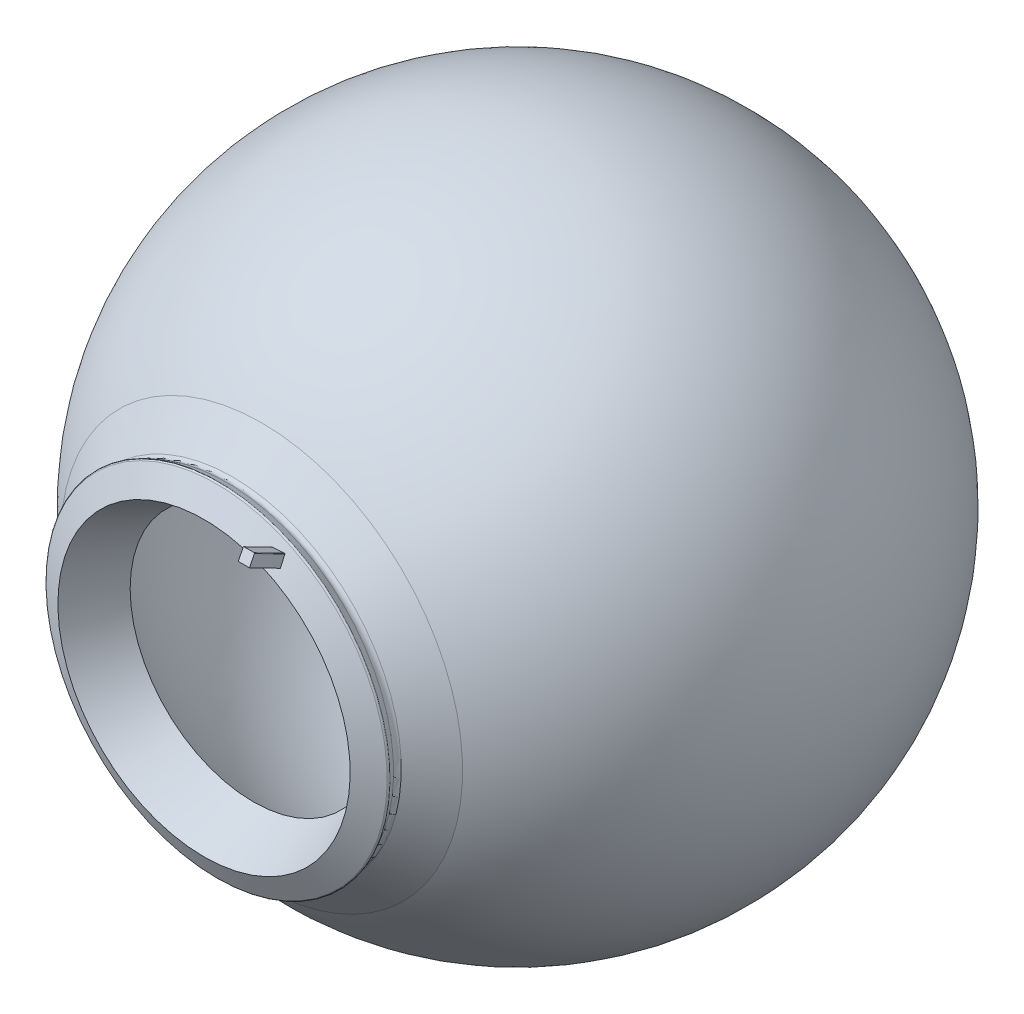
SolidWorks part; units mm, degrees
ref_plane "Front Plane" through (0, 0, 0) normal (0, 0, 1) x (1, 0, 0)
ref_plane "Top Plane" through (0, 0, 0) normal (0, 1, 0) x (1, 0, 0)
ref_plane "Right Plane" through (0, 0, 0) normal (1, 0, 0) x (0, 0, -1)
sketch "Sphere Sketch" plane through (0, 0, 0) normal (1, 0, 0) x (0, 0, -1)
  line L0 (-495, 0) -> (0, 0) construction
  line L1 (-495, 230.6517) -> (0, 0) construction
  line L2 (-495, 230.6517) -> (-495, 0) construction
  line L3 (-552.5581, 257.4717) -> (-495, 230.6517)
  line L5 (0, 0) -> (531.6016, 0) construction
  line L6 (-587.2743, 273.6481) -> (-552.5581, 257.4717)
  line L8 (-574.9857, 296.2531) -> (0, 0) construction
  line L9 (-856.9957, 1420.5972) -> (-601.6623, 1420.5972) construction
  line L11 (-563.7113, 319.3806) -> (-587.2743, 273.6481)
  line L12 (-479.5063, 376.4118) -> (-533.6922, 315.7211)
  line L13 (531.6016, 125) -> (531.6016, 0) construction
  line L14 (0, 0) -> (531.6016, 125) construction
  line L15 (-559.6704, 320.6734) -> (-545.714, 313.4825)
  line L17 (531.6016, 125) -> (593.4157, 139.5349)
  line L18 (593.4157, 139.5349) -> (618.1413, 145.3488)
  line L19 (618.1413, 145.3488) -> (568.3844, 220.3438)
  arc A2 (531.6016, 125) -> (-495, 230.6517) centre (0, 0) ccw
  arc A3 (-563.5933, 319.5888) -> (-587.2743, 273.6481) centre (0, 0) ccw construction
  arc A4 (568.3844, 220.3438) -> (-479.5063, 376.4118) centre (0, 0) ccw
  arc A5 (-533.6922, 315.7211) -> (-545.714, 313.4825) centre (-541.1517, 322.3812) cw
  arc A7 (-563.7113, 319.3806) -> (-559.6704, 320.6734) centre (-561.0445, 318.0066) cw
  point P24 (-479.5063, 376.4118)
  dimension "D1" = 495
  dimension "D2" = 609.6
  dimension "D3" = 546.1
  dimension "D4" = 647.9
  dimension "D6" = 15.7
  dimension "D8" = 10
  dimension "D9" = 104.5
  dimension "D10" = 125
  dimension "D11" = 635
  dimension "D5" = 3
  dimension "D7" = 51.4458
  dimension "D12" = 90
revolve "Sphere" add sketch "Sphere Sketch" angle 360 about L5
ref_plane "Hinge Plane" through (0, 296.5144, 575.4928) normal (0, 0.458, 0.8889) x (1, 0, 0)
sketch "Sketch1" plane through (0, 296.5144, 575.4928) normal (0, 0.458, 0.8889) x (1, 0, 0)
  line L0 (0, -25.7229) -> (123.8594, -25.7229) construction
  line L1 (0, 60.5405) -> (0, -60.5405) construction
  line L7 (114.4052, -36.4923) -> (134.3136, -36.4923)
  line L8 (0, -226.7177) -> (0, 0) construction
  line L13 (113.4052, -35.4923) -> (113.4052, -15.9535)
  line L14 (114.4052, -14.9535) -> (133.3136, -14.9535)
  line L15 (134.3136, -36.4923) -> (134.3136, -15.9535)
  line L16 (113.4052, -36.4923) -> (134.3136, -14.9535) construction
  line L17 (113.4052, -14.9535) -> (134.3136, -36.4923) construction
  arc A4 (134.3136, -15.9535) -> (133.3136, -14.9535) centre (133.3136, -15.9535) ccw
  arc A5 (114.4052, -14.9535) -> (113.4052, -15.9535) centre (114.4052, -15.9535) ccw
  arc A6 (113.4052, -35.4923) -> (114.4052, -36.4923) centre (114.4052, -35.4923) ccw
  ellipse E4 centre (0, -268.9808) end of major axis (-273.6481, -268.9808) minor radius 243.2579 construction
  point P5 (123.8594, -25.7229)
  point P17 (0, 0)
  dimension "D1" = 1
extrude "Boss-Extrude3" add sketch "Sketch1" along normal blind 50 and the other way blind 15
